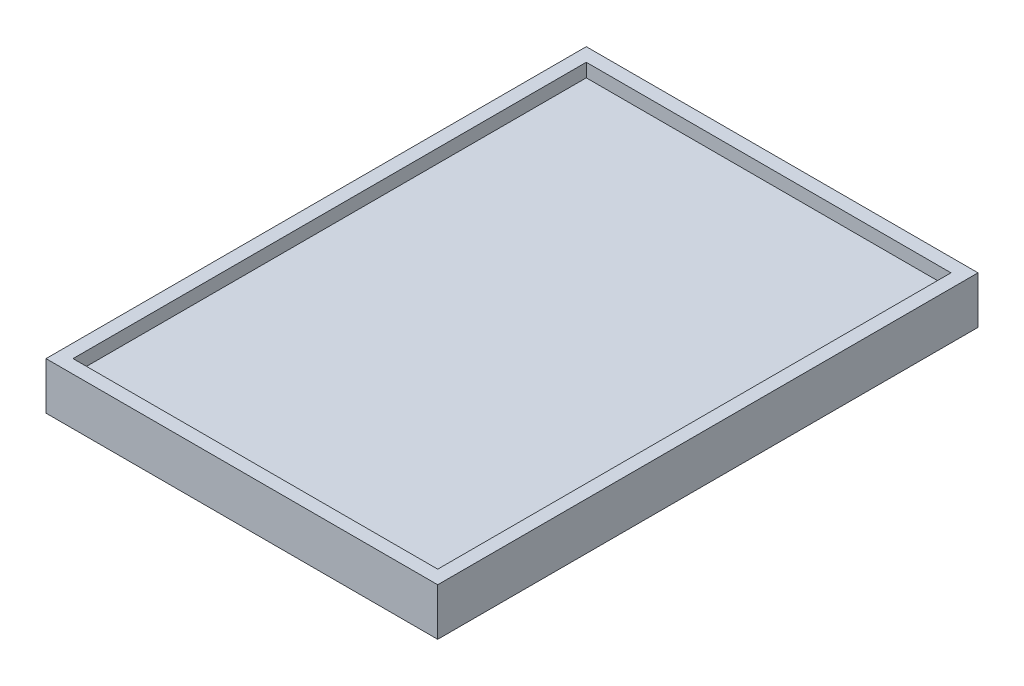
SolidWorks part; units mm, degrees
ref_plane "Front Plane" through (0, 0, 0) normal (0, 0, 1) x (1, 0, 0)
ref_plane "Top Plane" through (0, 0, 0) normal (0, 1, 0) x (1, 0, 0)
ref_plane "Right Plane" through (0, 0, 0) normal (1, 0, 0) x (0, 0, -1)
sketch "Sketch1" plane through (0, 0, 0) normal (0, 1, 0) x (1, 0, 0)
  line L1 (-145, 200) -> (145, 200)
  line L2 (-145, 200) -> (-145, -200)
  line L3 (-145, -200) -> (145, -200)
  line L4 (145, 200) -> (145, -200)
  line L5 (-145, 200) -> (145, -200) construction
  line L6 (-145, -200) -> (145, 200) construction
  point P0 (0, 0)
  dimension "D1" = 290
  dimension "D2" = 400
extrude "Boss-Extrude1" add sketch "Sketch1" along normal blind 35
sketch "Sketch2" plane through (0, 35, 0) normal (0, 1, 0) x (1, 0, 0)
  line L0 (145, -200) -> (145, 200) construction
  line L1 (-145, -200) -> (145, -200) construction
  line L2 (-145, 200) -> (-145, -200) construction
  line L3 (145, 200) -> (-145, 200) construction
  line L4 (145, -200) -> (145, 200)
  line L5 (-145, -200) -> (145, -200)
  line L6 (-145, 200) -> (-145, -200)
  line L7 (145, 200) -> (-145, 200)
  line L8 (135, -190) -> (135, 190)
  line L9 (135, 190) -> (-135, 190)
  line L10 (-135, 190) -> (-135, -190)
  line L11 (-135, -190) -> (135, -190)
  dimension "D1" = 10
extrude "Cut-Extrude2" cut sketch "Sketch2" against normal blind 10 contours L8 L9 L10 L11
sketch "Sketch3" plane through (0, 25, 0) normal (0, 1, 0) x (1, 0, 0)
  line L0 (0, 211.8692) -> (0, -222.8207) construction
  line L1 (-219.8723, 0) -> (201.339, 0) construction
  line L2 (135, 190) -> (-135, 190) construction
  line L3 (135, 190) -> (-135, 190) construction
  line L4 (135, 185) -> (-135, 185) construction
  line L5 (135, 165) -> (-135, 165) construction
  line L6 (-135, 190) -> (-135, -190) construction
  line L7 (-135, 190) -> (-135, -190) construction
  line L8 (-130, 190) -> (-130, -190) construction
  line L9 (-95, 190) -> (-95, -190) construction
  line L10 (-112.5, 190) -> (-112.5, -190) construction
  line L11 (-117.13, 185) -> (-101.75, 185)
  line L13 (-139, 190) -> (-139, -190)
  line L15 (-101.75, 199.739) -> (-101.75, 174.9169) construction
  line L16 (-99.4062, 166.62) -> (-99.4062, 165)
  line L17 (-101.75, 179.7) -> (-101.75, 185)
  line L18 (-125.5938, 165) -> (-99.4062, 165)
  line L19 (-125.5938, 166.62) -> (-125.5938, 165)
  line L20 (-123.25, 179.7) -> (-118.8793, 179.7)
  line L25 (-117.13, 185) -> (-117.13, 181.5)
  line L26 (-117.13, 181.5) -> (-118.8793, 179.7)
  arc A1 (-123.25, 179.7) -> (-125.5938, 166.62) centre (-123.25, 172.95) ccw
  arc A2 (-101.75, 179.7) -> (-99.4062, 166.62) centre (-101.75, 172.95) cw
  point P19 (0, 0)
  point P20 (135, 172.25)
  point P21 (-135, 173.09)
  point P24 (-126.7855, 190)
  point P25 (115.6811, -99.309)
  point P40 (-112.5, 165)
  dimension "D11" = 2.51
  dimension "D9" = 13.5
  dimension "D12" = 3.5
  dimension "D6" = 5.3
  dimension "D7" = 1.62
  dimension "D1" = 5
  dimension "D2" = 20
  dimension "D3" = 5
  dimension "D4" = 35
  dimension "D5" = 17.5
  dimension "D8" = 26.5
